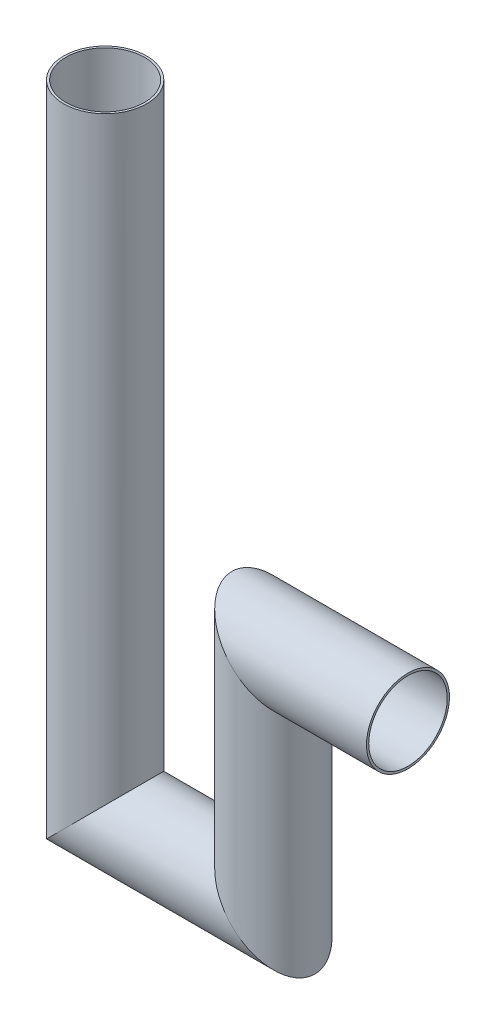
SolidWorks part; units mm, degrees
ref_plane "Front Plane" through (0, 0, 0) normal (0, 0, 1) x (1, 0, 0)
ref_plane "Top Plane" through (0, 0, 0) normal (0, 1, 0) x (1, 0, 0)
ref_plane "Right Plane" through (0, 0, 0) normal (1, 0, 0) x (0, 0, -1)
sketch "Sketch1" plane through (0, 0, 0) normal (0, 1, 0) x (1, 0, 0)
  circle A0 centre (0, 0) radius 44.45
  circle A1 centre (0, 0) radius 46.99
sketch3d "3DSketch1"
  line L0 (0, 0, 0) -> (0, -711.2, 0)
  line L1 (0, -711.2, 0) -> (190.5, -711.2, 0)
  line L2 (190.5, -711.2, 0) -> (190.5, -457.2, 0)
  line L3 (190.5, -457.2, 0) -> (342.9, -457.2, 0)
sweep "Sweep2" add profiles "Sketch1" path "3DSketch1"
